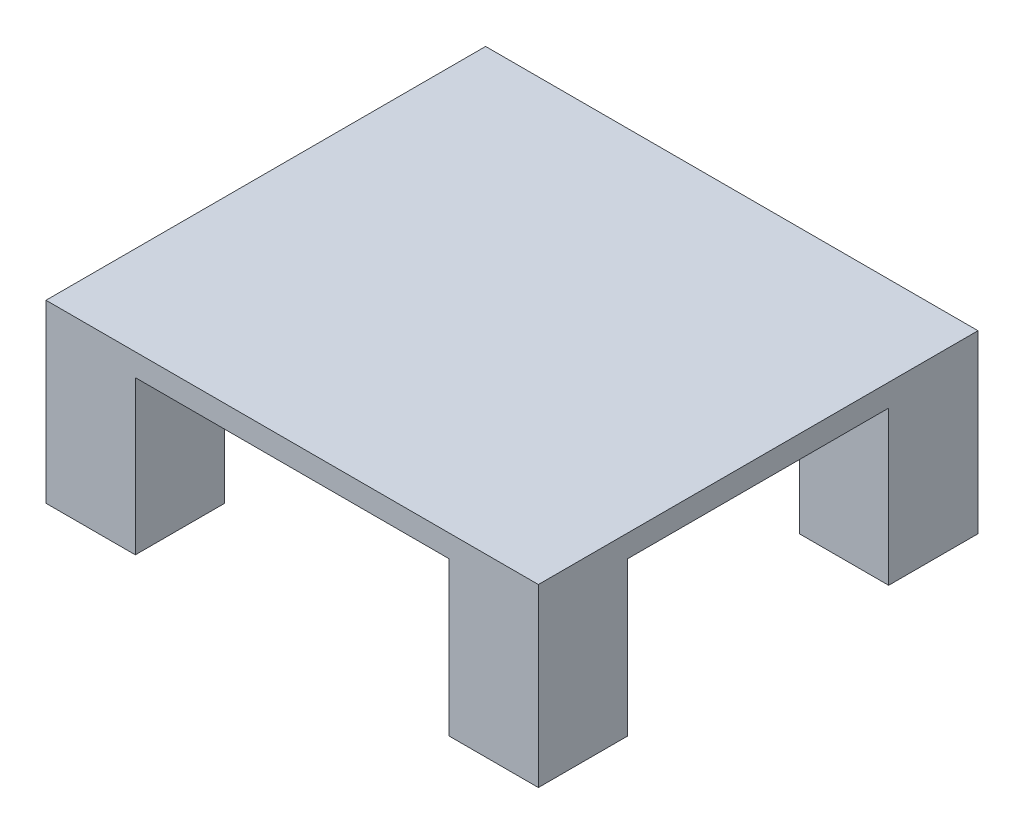
SolidWorks part; units mm, degrees
ref_plane "Alzado" through (0, 0, 0) normal (0, 0, 1) x (1, 0, 0)
ref_plane "Planta" through (0, 0, 0) normal (0, 1, 0) x (1, 0, 0)
ref_plane "Vista lateral" through (0, 0, 0) normal (1, 0, 0) x (0, 0, -1)
sketch "Croquis1" plane through (0, 0, 0) normal (0, 1, 0) x (1, 0, 0)
  line L0 (50.8, 0) -> (140, 0) construction
  line L1 (0, 0) -> (50.8, 0)
  line L2 (0, 0) -> (0, -50.8)
  line L3 (0, -50.8) -> (50.8, -50.8)
  line L4 (50.8, 0) -> (50.8, -50.8)
  line L5 (140, 0) -> (140, -125) construction
  line L6 (140, -125) -> (0, -125) construction
  line L7 (0, -125) -> (0, -50.8) construction
  line L8 (229.2, 0) -> (229.2, -50.8)
  line L9 (280, -50.8) -> (229.2, -50.8)
  line L10 (280, 0) -> (280, -50.8)
  line L11 (280, 0) -> (229.2, 0)
  line L12 (50.8, -250) -> (140, -250) construction
  line L13 (280, -250) -> (229.2, -250)
  line L14 (280, -250) -> (280, -199.2)
  line L15 (280, -199.2) -> (229.2, -199.2)
  line L16 (229.2, -250) -> (229.2, -199.2)
  line L17 (50.8, -250) -> (50.8, -199.2)
  line L18 (0, -199.2) -> (50.8, -199.2)
  line L19 (0, -250) -> (0, -199.2)
  line L20 (0, -250) -> (50.8, -250)
  dimension "D1" = 50.8
  dimension "D2" = 50.8
  dimension "D3" = 140
  dimension "D4" = 125
extrude "Saliente-Extruir1" add sketch "Croquis1" along normal blind 100
sketch "Croquis2" plane through (0, 0, 250) normal (0, 0, 1) x (1, 0, 0)
  line L0 (280, 100) -> (280, 0) construction
  line L1 (0, 100) -> (280, 100)
  line L2 (0, 100) -> (0, 87.3)
  line L3 (0, 87.3) -> (280, 87.3)
  line L4 (280, 100) -> (280, 87.3)
  dimension "D1" = 12.7
extrude "Saliente-Extruir2" add sketch "Croquis2" against normal up to surface (250 mm away) up to face at (254.6, 50, 0)
